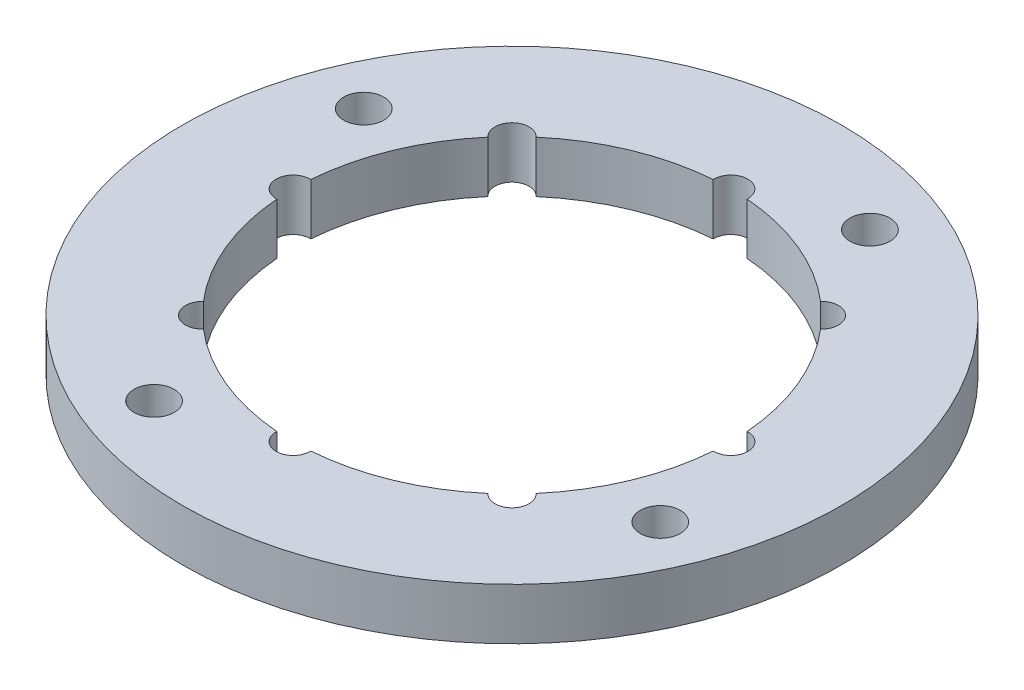
SolidWorks part; units mm, degrees
ref_plane "Front Plane" through (0, 0, 0) normal (0, 0, 1) x (1, 0, 0)
ref_plane "Top Plane" through (0, 0, 0) normal (0, 1, 0) x (1, 0, 0)
ref_plane "Right Plane" through (0, 0, 0) normal (1, 0, 0) x (0, 0, -1)
sketch "1.5in Socket" plane through (0, 0, 0) normal (0, 1, 0) x (1, 0, 0)
  line L0 (0, 0) -> (-19.083, 19.083) construction
  line L1 (0, 26.9875) -> (0, 0)
  line L2 (19.083, 19.083) -> (0, 0) construction
  line L3 (26.9875, 0) -> (0, 0)
  line L4 (19.083, -19.083) -> (0, 0) construction
  line L5 (0, -26.9875) -> (0, 0)
  line L6 (-19.083, -19.083) -> (0, 0) construction
  line L7 (-26.9875, 0) -> (0, 0) construction
  line L8 (-12.9278, -31.2105) -> (0, 0) construction
  line L9 (-31.2105, 12.9278) -> (0, 0) construction
  line L10 (31.2105, -12.9278) -> (0, 0) construction
  line L11 (12.9278, 31.2105) -> (0, 0) construction
  circle A0 centre (0, 0) radius 40.64
  arc A1 (-2.0939, 26.9061) -> (2.0939, 26.9061) centre (0, 26.9875) cw
  arc A2 (2.0939, 26.9061) -> (17.5449, 20.5061) centre (0, 0) cw
  arc A3 (17.5449, 20.5061) -> (20.5061, 17.5449) centre (19.083, 19.083) cw
  arc A4 (20.5061, 17.5449) -> (26.9061, 2.0939) centre (0, 0) cw
  arc A5 (26.9061, 2.0939) -> (26.9061, -2.0939) centre (26.9875, 0) cw
  arc A6 (26.9061, -2.0939) -> (20.5061, -17.5449) centre (0, 0) cw
  arc A7 (20.5061, -17.5449) -> (17.5449, -20.5061) centre (19.083, -19.083) cw
  arc A8 (17.5449, -20.5061) -> (2.0939, -26.9061) centre (0, 0) cw
  arc A9 (2.0939, -26.9061) -> (-2.0939, -26.9061) centre (0, -26.9875) cw
  arc A10 (-2.0939, -26.9061) -> (-17.5449, -20.5061) centre (0, 0) cw
  arc A11 (-17.5449, -20.5061) -> (-20.5061, -17.5449) centre (-19.083, -19.083) cw
  arc A12 (-20.5061, -17.5449) -> (-26.9061, -2.0939) centre (0, 0) cw
  arc A13 (-26.9061, -2.0939) -> (-26.9061, 2.0939) centre (-26.9875, 0) cw
  arc A14 (-26.9061, 2.0939) -> (-20.5061, 17.5449) centre (0, 0) cw
  arc A15 (-20.5061, 17.5449) -> (-17.5449, 20.5061) centre (-19.083, 19.083) cw
  arc A16 (-17.5449, 20.5061) -> (-2.0939, 26.9061) centre (0, 0) cw
  arc A18 (-2.0939, 26.9061) -> (-17.5449, 20.5061) centre (0, 0) ccw
  arc A19 (-17.5449, 20.5061) -> (-20.5061, 17.5449) centre (-19.083, 19.083) ccw
  arc A20 (-20.5061, 17.5449) -> (-26.9061, 2.0939) centre (0, 0) ccw
  arc A21 (-26.9061, 2.0939) -> (-26.9061, -2.0939) centre (-26.9875, 0) ccw
  arc A22 (-26.9061, -2.0939) -> (-20.5061, -17.5449) centre (0, 0) ccw
  arc A23 (-20.5061, -17.5449) -> (-17.5449, -20.5061) centre (-19.083, -19.083) ccw
  arc A24 (-17.5449, -20.5061) -> (-2.0939, -26.9061) centre (0, 0) ccw
  arc A25 (-2.0939, -26.9061) -> (2.0939, -26.9061) centre (0, -26.9875) ccw
  arc A26 (2.0939, -26.9061) -> (17.5449, -20.5061) centre (0, 0) ccw
  arc A27 (17.5449, -20.5061) -> (20.5061, -17.5449) centre (19.083, -19.083) ccw
  arc A28 (20.5061, -17.5449) -> (26.9061, -2.0939) centre (0, 0) ccw
  arc A29 (26.9061, -2.0939) -> (26.9061, 2.0939) centre (26.9875, 0) ccw
  arc A30 (26.9061, 2.0939) -> (20.5061, 17.5449) centre (0, 0) ccw
  arc A31 (20.5061, 17.5449) -> (17.5449, 20.5061) centre (19.083, 19.083) ccw
  arc A32 (17.5449, 20.5061) -> (2.0939, 26.9061) centre (0, 0) ccw
  arc A33 (2.0939, 26.9061) -> (-2.0939, 26.9061) centre (0, 26.9875) ccw
  circle A34 centre (-12.9278, -31.2105) radius 2.475
  circle A35 centre (-31.2105, 12.9278) radius 2.475
  circle A36 centre (31.2105, -12.9278) radius 2.475
  circle A37 centre (12.9278, 31.2105) radius 2.475
  point P27 (-19.083, -19.083)
  point P28 (-26.9875, 0)
  point P29 (0, 0)
  point P30 (0, -26.9875)
  point P31 (19.083, -19.083)
  point P32 (26.9875, 0)
  point P33 (19.083, 19.083)
  point P34 (0, 26.9875)
  point P35 (-19.083, 19.083)
  point P36 (0, 0)
  dimension "D1" = 2.0955
  dimension "D2" = 2.0955
  dimension "D3" = 2.0955
  dimension "D4" = 2.0955
  dimension "D5" = 2.0955
  dimension "D6" = 2.0955
  dimension "D7" = 2.0955
  dimension "D8" = 2.0955
  dimension "D9" = 26.9875
  dimension "D10" = 26.9875
  dimension "D11" = 26.9875
  dimension "D12" = 26.9875
  dimension "D13" = 26.9875
  dimension "D14" = 26.9875
  dimension "D15" = 26.9875
  dimension "D16" = 26.9875
  dimension "D17" = 81.28
  dimension "D26" = 4.95
  dimension "D28" = 33.782
  dimension "D30" = 4.95
  dimension "D31" = 4.95
  dimension "D32" = 4.95
  dimension "D18" = 26.9875
  dimension "D19" = 26.9875
  dimension "D20" = 26.9875
  dimension "D21" = 26.9875
  dimension "D22" = 26.9875
  dimension "D23" = 26.9875
  dimension "D24" = 26.9875
  dimension "D25" = 26.9875
  dimension "D27" = 33.782
  dimension "D29" = 90
  dimension "D33" = 90
  dimension "D34" = 90
  dimension "D35" = 33.782
  dimension "D36" = 33.782
  dimension "D37" = 67.5
extrude "Boss-Extrude1" add sketch "1.5in Socket" along normal blind 6.35 contours A0 A37 A36 A35 A34 A15 A16 A1 A2 A3 A4 A5 A6 A7 A8 A9 A10 A11 A12 A13 A14
